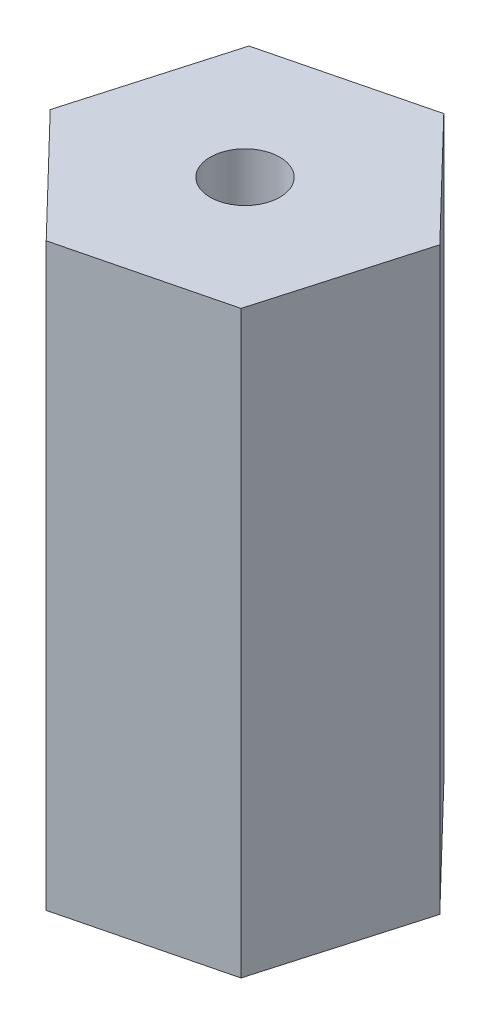
SolidWorks part; units mm, degrees
material "ABS"
ref_plane "Plano frontal" through (0, 0, 0) normal (0, 0, 1) x (1, 0, 0)
ref_plane "Plano superior" through (0, 0, 0) normal (0, 1, 0) x (1, 0, 0)
ref_plane "Plano direito" through (0, 0, 0) normal (1, 0, 0) x (0, 0, -1)
sketch "Esboço1" plane through (0, 0, 0) normal (0, 1, 0) x (1, 0, 0)
  line L1 (4.8123, -4.9842) -> (6.7226, 1.6755)
  line L2 (6.7226, 1.6755) -> (1.9103, 6.6596)
  line L3 (1.9103, 6.6596) -> (-4.8123, 4.9842)
  line L4 (-4.8123, 4.9842) -> (-6.7226, -1.6755)
  line L5 (-6.7226, -1.6755) -> (-1.9103, -6.6596)
  line L6 (-1.9103, -6.6596) -> (4.8123, -4.9842)
  circle A0 centre (0, 0) radius 6 construction
extrude "Ressalto-extrusão1" add sketch "Esboço1" along normal blind 25
sketch "Esboço2" plane through (0, 0, 0) normal (0, -1, 0) x (1, 0, 0)
  circle A0 centre (0, 0) radius 1.5
extrude "Corte-extrusão1" cut sketch "Esboço2" against normal blind 30
